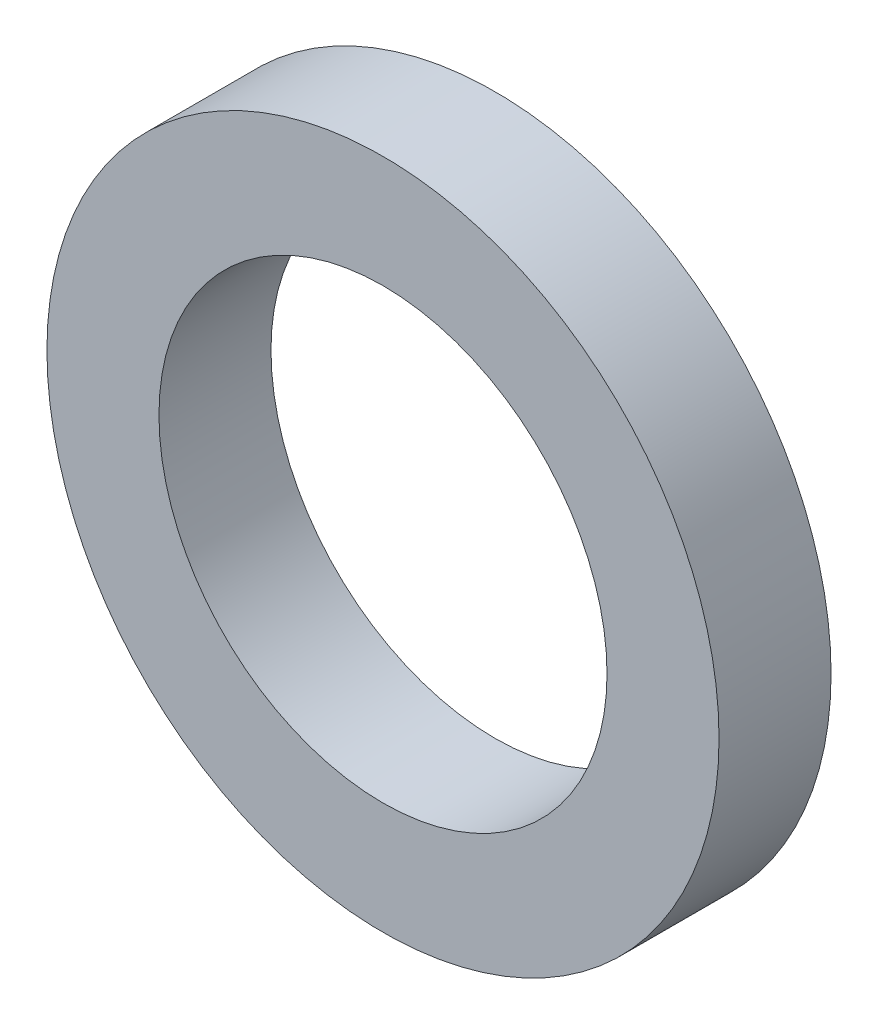
SolidWorks part; units mm, degrees
material "Custom Plastic"
ref_plane "Left Plane" through (0, 0, 0) normal (0, 0, 1) x (1, 0, 0)
ref_plane "Top Plane" through (0, 0, 0) normal (0, 1, 0) x (1, 0, 0)
ref_plane "Right Plane" through (0, 0, 0) normal (1, 0, 0) x (0, 0, -1)
sketch "Sketch1" plane through (0, 0, 0) normal (0, 0, 1) x (1, 0, 0)
  circle A0 centre (0, 0) radius 3
extrude "PLA_washer" add sketch "Sketch1" along normal blind 1
sketch "Sketch2" plane through (0, 0, 1) normal (0, 0, 1) x (1, 0, 0)
  circle A0 centre (0, 0) radius 2
extrude "Cut-Extrude1" cut sketch "Sketch2" against normal through all
